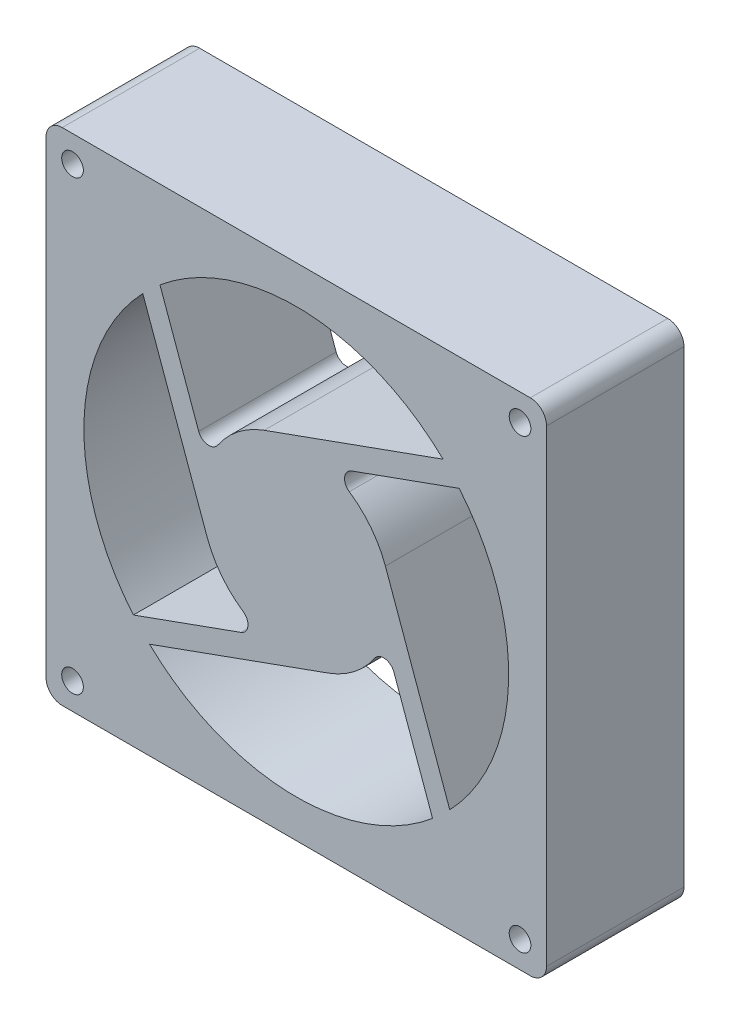
SolidWorks part; units mm, degrees
ref_plane "Спереди" through (0, 0, 0) normal (0, 0, 1) x (1, 0, 0)
ref_plane "Сверху" through (0, 0, 0) normal (0, 1, 0) x (1, 0, 0)
ref_plane "Справа" through (0, 0, 0) normal (1, 0, 0) x (0, 0, -1)
sketch "Эскиз1" plane through (0, 0, 0) normal (0, 0, 1) x (1, 0, 0)
  line L0 (-41.35, 41.35) -> (41.35, 41.35) construction
  line L1 (-46.25, 46.25) -> (46.25, 46.25)
  line L2 (-46.25, 46.25) -> (-46.25, -46.25)
  line L3 (-46.25, -46.25) -> (46.25, -46.25)
  line L4 (46.25, 46.25) -> (46.25, -46.25)
  line L5 (41.35, 41.35) -> (41.35, -41.35) construction
  line L6 (41.35, -41.35) -> (-41.35, -41.35) construction
  line L7 (-41.35, -41.35) -> (-41.35, 41.35) construction
  line L8 (46.25, 35.25) -> (-5.9277, 16.4655) construction
  line L9 (46.25, 30.9987) -> (5.9044, 16.4739) construction
  line L10 (35.25, -46.25) -> (16.4655, 5.9277) construction
  line L11 (30.1037, 25.1859) -> (10.2442, 18.0362)
  line L12 (16.4655, 5.9277) -> (28.3659, -27.1281)
  line L13 (5.9277, -16.4655) -> (-27.1281, -28.3659)
  line L14 (25.1859, -30.1037) -> (18.0362, -10.2442)
  line L15 (-16.4655, -5.9277) -> (-28.3659, 27.1281)
  line L16 (-30.1037, -25.1859) -> (-10.2442, -18.0362)
  line L17 (-5.9277, 16.4655) -> (27.1281, 28.3659)
  line L18 (-25.1859, 30.1037) -> (-18.0362, 10.2442)
  circle A0 centre (-41.35, 41.35) radius 2
  circle A1 centre (-41.35, -41.35) radius 2
  circle A2 centre (41.35, -41.35) radius 2
  circle A3 centre (41.35, 41.35) radius 2
  circle A4 centre (0, 0) radius 39.25 construction
  circle A5 centre (0, 0) radius 17.5 construction
  circle A6 centre (10.9217, 16.1545) radius 2 construction
  arc A7 (10.2442, 18.0362) -> (9.8015, 14.4976) centre (10.9217, 16.1545) ccw
  arc A8 (9.8015, 14.4976) -> (16.4655, 5.9277) centre (0, 0) cw
  arc A9 (28.3659, -27.1281) -> (30.1037, 25.1859) centre (0, 0) ccw
  arc A10 (-27.1281, -28.3659) -> (25.1859, -30.1037) centre (0, 0) ccw
  arc A11 (18.0362, -10.2442) -> (14.4976, -9.8015) centre (16.1545, -10.9217) ccw
  arc A12 (14.4976, -9.8015) -> (5.9277, -16.4655) centre (0, 0) cw
  arc A13 (-28.3659, 27.1281) -> (-30.1037, -25.1859) centre (0, 0) ccw
  arc A14 (-10.2442, -18.0362) -> (-9.8015, -14.4976) centre (-10.9217, -16.1545) ccw
  arc A15 (-9.8015, -14.4976) -> (-16.4655, -5.9277) centre (0, 0) cw
  arc A16 (27.1281, 28.3659) -> (-25.1859, 30.1037) centre (0, 0) ccw
  arc A17 (-18.0362, 10.2442) -> (-14.4976, 9.8015) centre (-16.1545, 10.9217) ccw
  arc A18 (-14.4976, 9.8015) -> (-5.9277, 16.4655) centre (0, 0) cw
  point P13 (-41.35, 0)
  point P15 (0, 41.35)
  point P16 (-46.25, 0)
  point P17 (0, 46.25)
  point P53 (0, 0)
  dimension "D3" = 4
  dimension "D4" = 78.5
  dimension "D5" = 35
  dimension "D8" = 4
  dimension "D1" = 82.7
  dimension "D2" = 92.5
  dimension "D6" = 11
  dimension "D7" = 4
  dimension "D9" = 11
  dimension "D10" = 4
extrude "Бобышка-Вытянуть1" add sketch "Эскиз1" along normal blind 25.4
fillet "Скругление2" radius 3 4 edges at (-46.25, -46.25, 12.7) (46.25, -46.25, 12.7) (-46.25, 46.25, 12.7) (46.25, 46.25, 12.7)
